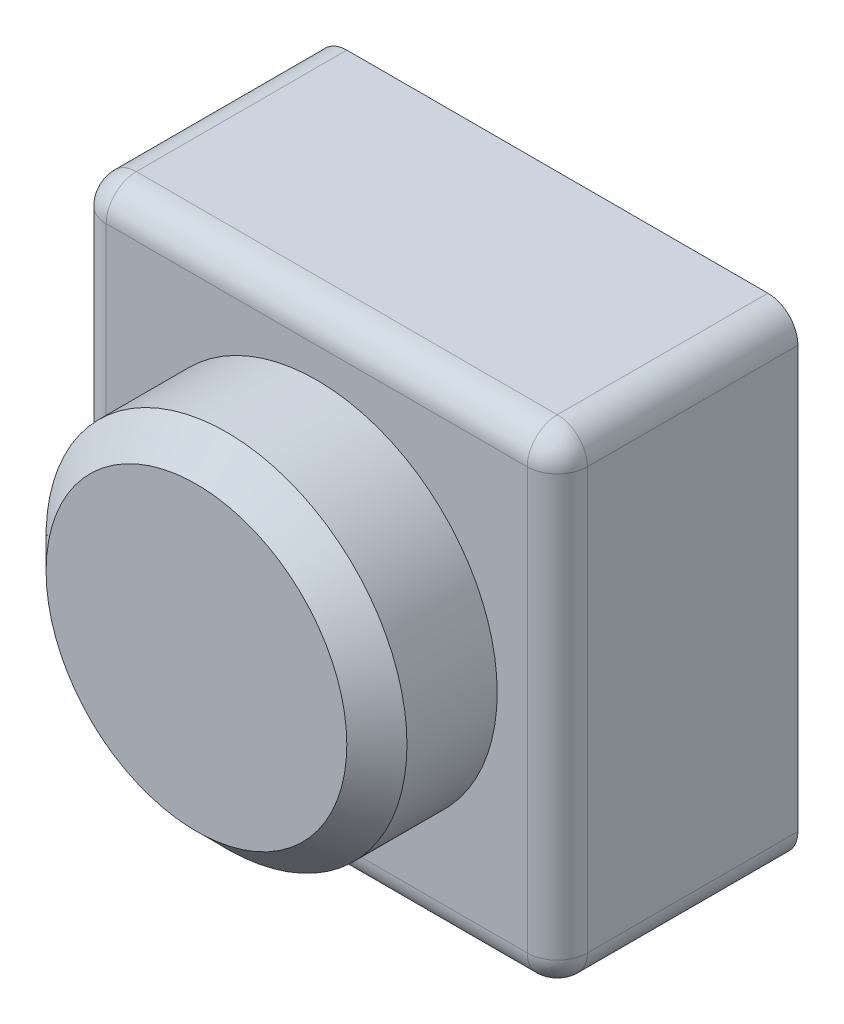
SolidWorks part; units mm, degrees
ref_plane "前视基准面" through (0, 0, 0) normal (0, 0, 1) x (1, 0, 0)
ref_plane "上视基准面" through (0, 0, 0) normal (0, 1, 0) x (1, 0, 0)
ref_plane "右视基准面" through (0, 0, 0) normal (1, 0, 0) x (0, 0, -1)
sketch "草图1" plane through (0, 0, 0) normal (0, 0, 1) x (1, 0, 0)
  line L1 (-40, -40) -> (40, -40)
  line L2 (-40, -40) -> (-40, 40)
  line L3 (-40, 40) -> (40, 40)
  line L4 (40, -40) -> (40, 40)
  line L5 (-40, -40) -> (40, 40) construction
  line L6 (-40, 40) -> (40, -40) construction
  point P0 (0, 0)
extrude "凸台-拉伸1" add sketch "草图1" along normal blind 40
sketch "草图2" plane through (0, 0, 40) normal (0, 0, 1) x (1, 0, 0)
  circle A0 centre (0, 0) radius 30
extrude "凸台-拉伸2" add sketch "草图2" along normal blind 20
sketch "草图3" plane through (0, 0, 0) normal (0, 0, -1) x (-1, 0, 0)
  line L1 (-30, -30) -> (30, -30)
  line L2 (-30, -30) -> (-30, 30)
  line L3 (-30, 30) -> (30, 30)
  line L4 (30, -30) -> (30, 30)
  line L5 (-30, -30) -> (30, 30) construction
  line L6 (-30, 30) -> (30, -30) construction
  point P0 (0, 0)
extrude "切除-拉伸1" cut sketch "草图3" against normal blind 30
sketch "草图4" plane through (0, 0, 30) normal (0, 0, -1) x (-1, 0, 0)
  circle A0 centre (0, 0) radius 20
extrude "切除-拉伸2" cut sketch "草图4" against normal blind 20
chamfer "倒角1" distance 5 angle 45 1 edges at (30, 0, 60)
fillet "圆角1" radius 5 8 edges at (40, 40, 20) (40, -40, 20) (-40, -40, 20) (-40, 40, 20) (40, 0, 40) (0, -40, 40) (-40, 0, 40) (0, 40, 40)
